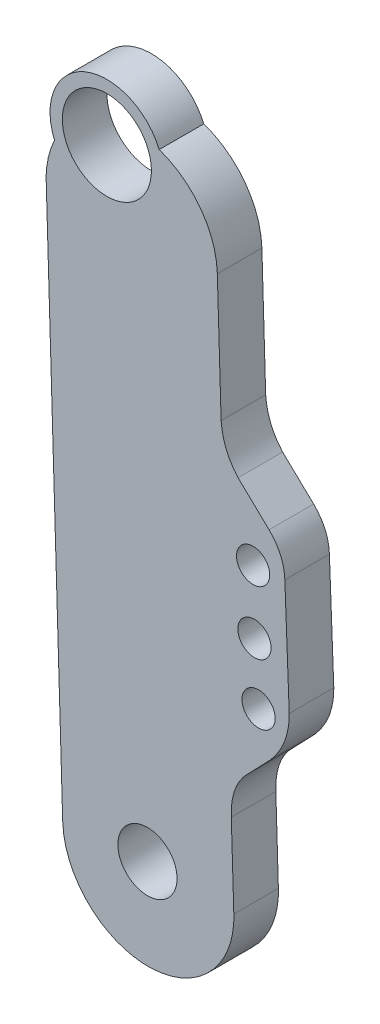
SolidWorks part; units mm, degrees
ref_plane "Front Plane" through (0, 0, 0) normal (0, 0, 1) x (1, 0, 0)
ref_plane "Top Plane" through (0, 0, 0) normal (0, 1, 0) x (1, 0, 0)
ref_plane "Right Plane" through (0, 0, 0) normal (1, 0, 0) x (0, 0, -1)
sketch "Sketch1" plane through (0, 0, 0) normal (0, 0, 1) x (1, 0, 0)
  line L0 (-382.5197, 101.6715) -> (-380.6694, 40.3691)
  line L1 (-361.4663, 40.9487) -> (-361.7508, 50.2285)
  line L2 (-359.834, 55.4154) -> (-357.3344, 58.0139)
  line L3 (-355.2484, 63.5578) -> (-355.7406, 76.291)
  line L4 (-357.5097, 80.2789) -> (-360.9895, 83.5907)
  line L5 (-362.8924, 88.201) -> (-363.3165, 102.2511)
  circle A0 centre (-371.1569, 41.2109) radius 3.3195
  circle A1 centre (-359.3035, 75.9188) radius 1.8602
  circle A2 centre (-359.1501, 68.8968) radius 1.8664
  circle A4 centre (-358.6909, 62.2771) radius 1.8626
  circle A6 centre (-375.7128, 108.5729) radius 5
  arc A7 (-369.8405, 111.0573) -> (-381.5852, 106.0885) centre (-375.7128, 108.5729) ccw
  spline S12 degree 3 poles (-380.6694, 40.3691) (-380.5101, 35.0882) (-376.059, 30.8979) (-370.7781, 31.0573) knots 0.052632 0.052632 0.052632 0.052632 0.105263 0.105263 0.105263 0.105263
  spline S13 degree 3 poles (-370.7781, 31.0573) (-365.4972, 31.2167) (-361.3044, 35.6679) (-361.4663, 40.9487) knots 0.157895 0.157895 0.157895 0.157895 0.210526 0.210526 0.210526 0.210526
  spline S14 degree 3 poles (-361.7508, 50.2285) (-361.8358, 52.3936) (-361.1804, 54.1127) (-359.834, 55.4154) knots 0.263158 0.263158 0.263158 0.263158 0.315789 0.315789 0.315789 0.315789
  spline S15 degree 3 poles (-357.3344, 58.0139) (-355.9919, 59.5715) (-355.2275, 61.3885) (-355.2484, 63.5578) knots 0.368421 0.368421 0.368421 0.368421 0.421053 0.421053 0.421053 0.421053
  spline S16 degree 3 poles (-355.7406, 76.291) (-355.7924, 77.8128) (-356.3667, 79.1476) (-357.5097, 80.2789) knots 0.473684 0.473684 0.473684 0.473684 0.526316 0.526316 0.526316 0.526316
  spline S17 degree 3 poles (-360.9895, 83.5907) (-362.2093, 84.9395) (-362.7614, 86.5026) (-362.8924, 88.201) knots 0.578947 0.578947 0.578947 0.578947 0.631579 0.631579 0.631579 0.631579
  spline S18 degree 3 poles (-363.3165, 102.2511) (-363.4404, 106.3554) (-366.157, 109.8006) (-369.8405, 111.0573) knots 0.684211 0.684211 0.684211 0.684211 0.736842 0.736842 0.736842 0.736842
  spline S22 degree 3 poles (-381.5852, 106.0885) (-382.2266, 104.7516) (-382.5673, 103.2487) (-382.5197, 101.6715) knots 0.894737 0.894737 0.894737 0.894737 1 1 1 1
  dimension "D2" = 10
  dimension "D1" = 80
extrude "Boss-Extrude1" add sketch "Sketch1" along normal blind 5
scale "Scale1" scale about centroid uniform scaling yes scale factor 1.5
